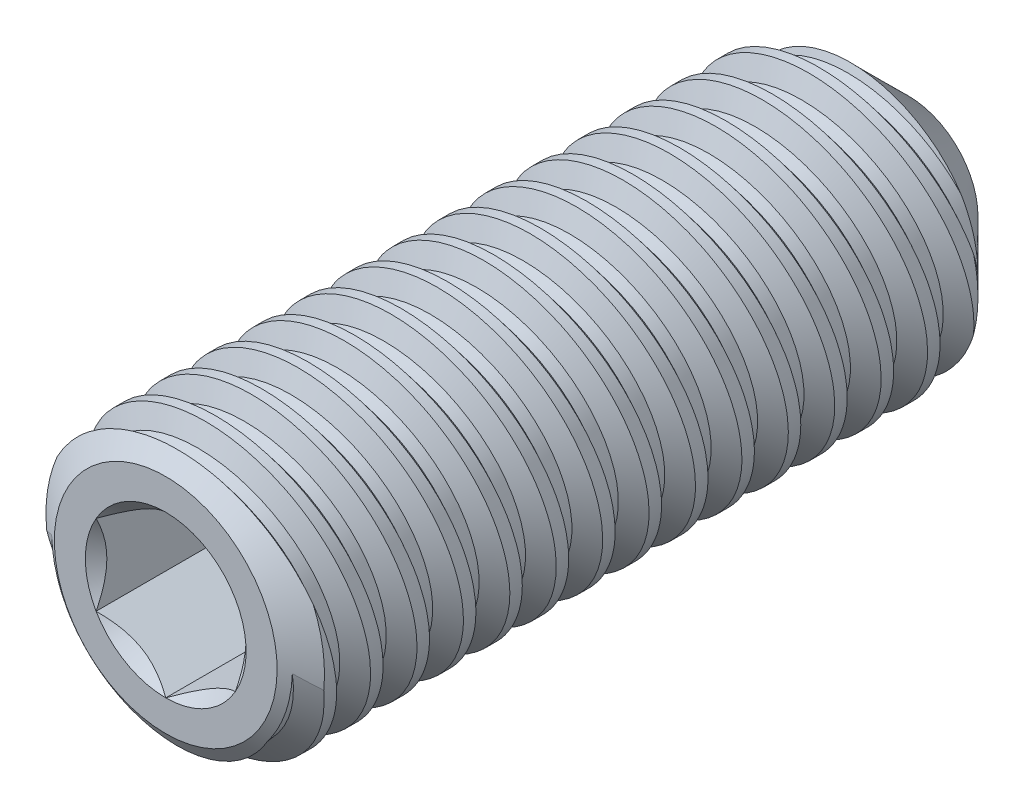
SolidWorks part; units mm, degrees
ref_plane "Front" through (0, 0, 0) normal (0, 0, 1) x (1, 0, 0)
ref_plane "Top" through (0, 0, 0) normal (0, 1, 0) x (1, 0, 0)
ref_plane "Right" through (0, 0, 0) normal (1, 0, 0) x (0, 0, -1)
sketch "Sketch22" plane through (0, 0, 0) normal (1, 0, 0) x (0, 0, -1)
  line L0 (-3.7747, 0) -> (-3.7747, 1.2)
  line L1 (-3.7747, 1.2) -> (-3.5646, 1.5)
  line L2 (-3.5646, 1.5) -> (3.4753, 1.5)
  line L3 (3.4753, 1.5) -> (4.2253, 0.75)
  line L4 (4.2253, 0.75) -> (3.7747, 0)
  line L5 (3.7747, 0) -> (-3.7747, 0)
  line L6 (3.7747, 0) -> (4.2253, 0) construction
  line L7 (4.2253, 0) -> (4.2253, 0.75) construction
  line L8 (4.2253, -0.75) -> (3.7747, 0) construction
  line L9 (-3.5646, -1.5) -> (3.4753, -1.5) construction
  dimension "Screw Dia" = 3
  dimension "Length" = 8
  dimension "D3" = 35
  dimension "Cup Point Dia" = 1.5
  dimension "D5" = 118
  dimension "D6" = 45
  dimension "D7" = 2.4
revolve "Revolve1" add sketch "Sketch22" angle 360 about L6
sketch "Sketch6" plane through (0, 0, 0) normal (1, 0, 0) x (0, 0, -1)
  line L0 (2.6902, 1.5) -> (3.1902, -1.5) construction
  line L1 (-3.5646, 1.5) -> (3.4753, 1.5) construction
  line L2 (-3.5646, -1.5) -> (3.4753, -1.5) construction
  line L3 (2.6902, 1.5) -> (2.7518, 1.5103) construction
  line L4 (3.0738, 1.2896) -> (2.9505, 1.269)
  line L5 (2.9505, 1.269) -> (2.7518, 1.5103)
  line L6 (3.0738, 1.2896) -> (3.1834, 1.5822)
  line L7 (3.1834, 1.5822) -> (2.7518, 1.5103)
  line L8 (2.9753, 1.5) -> (3.4753, -1.5) construction
  line L9 (3.7605, 0.0892) -> (2.6902, -0.0892) construction
  line L10 (2.9676, 1.5462) -> (3.0121, 1.2793) construction
  line L13 (2.6902, -1.5) -> (2.6902, 1.5) construction
  line L14 (2.6902, -1.5) -> (3.1902, -1.5) construction
  line L15 (3.1902, -1.5) -> (3.4753, -1.5) construction
  line L18 (2.6902, 1.5) -> (2.9753, 1.5) construction
  point P18 (3.2253, 0)
  dimension "D1" = 0.5
  dimension "D2" = 0.125
  dimension "D3" = 60
  dimension "D4" = 0.0625
  dimension "Pitch" = 0.5
revolve "Cut-Revolve8" cut sketch "Sketch6" angle 360 about L9
pattern_linear "LPattern1" count 15 spacing 0.5 along (0, 0, 1) count 2 spacing 0.5 along (0, 0, -1) of "Cut-Revolve8"
sketch "Sketch23" plane through (0, 0, 3.7747) normal (0, 0, 1) x (1, 0, 0)
  line L1 (0, 0.866) -> (-0.75, 0.433)
  line L2 (-0.75, 0.433) -> (-0.75, -0.433)
  line L3 (-0.75, -0.433) -> (0, -0.866)
  line L4 (0, -0.866) -> (0.75, -0.433)
  line L5 (0.75, -0.433) -> (0.75, 0.433)
  line L6 (0.75, 0.433) -> (0, 0.866)
  circle A0 centre (0, 0) radius 0.75 construction
  dimension "Hex" = 1.5
extrude "Cut-Extrude10" cut sketch "Sketch23" against normal blind 1.5
sketch "Sketch24" plane through (0, 0, 3.7747) normal (0, 0, 1) x (1, 0, 0)
  circle A0 centre (0, 0) radius 0.866
extrude "Cut-Extrude11" cut sketch "Sketch24" against normal through all draft 45
sketch "Sketch26" plane through (0, 0, 2.2747) normal (0, 0, 1) x (1, 0, 0)
  circle A0 centre (0, 0) radius 0.75 construction
  circle A1 centre (0, 0) radius 0.75
extrude "Cut-Extrude12" cut sketch "Sketch26" against normal through all draft 59
equation "\"D2@Sketch6\"=\"Pitch@Sketch6\"/4"
equation "\"D4@Sketch6\"=\"Pitch@Sketch6\"/8"
equation "\"D1@Sketch6\"=\"Pitch@Sketch6\""
equation "\"D3@LPattern1\"=\"Pitch@Sketch6\""
equation "\"D1@LPattern1\"=(\"Length@Sketch22\"/\"Pitch@Sketch6\")-1"
equation "\"D4@LPattern1\"=\"Pitch@Sketch6\""
equation "\"D7@Sketch22\"=\"Screw Dia@Sketch22\"*.8"
